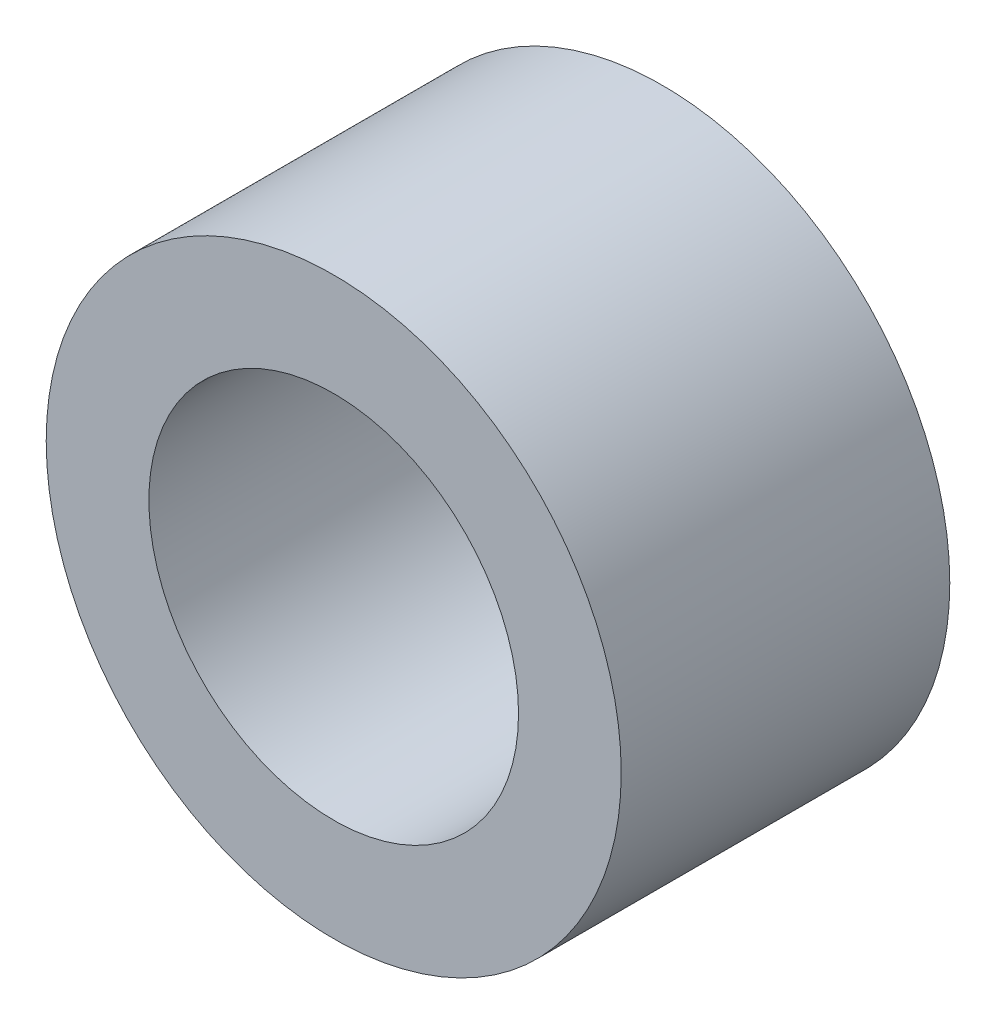
SolidWorks part; units mm, degrees
ref_plane "Front Plane" through (0, 0, 0) normal (0, 0, 1) x (1, 0, 0)
ref_plane "Top Plane" through (0, 0, 0) normal (0, 1, 0) x (1, 0, 0)
ref_plane "Right Plane" through (0, 0, 0) normal (1, 0, 0) x (0, 0, -1)
sketch "Sketch1" plane through (0, 0, 0) normal (0, 0, 1) x (1, 0, 0)
  circle A0 centre (0, 0) radius 3.5
  dimension "D1" = 7
extrude "Boss-Extrude1" add sketch "Sketch1" against normal blind 4
sketch "Sketch11" plane through (0, 0, 0) normal (0, 0, 1) x (1, 0, 0)
  circle A0 centre (0, 0) radius 2.25
  dimension "D1" = 4.5
extrude "Cut-Extrude1" cut sketch "Sketch11" against normal blind 4
